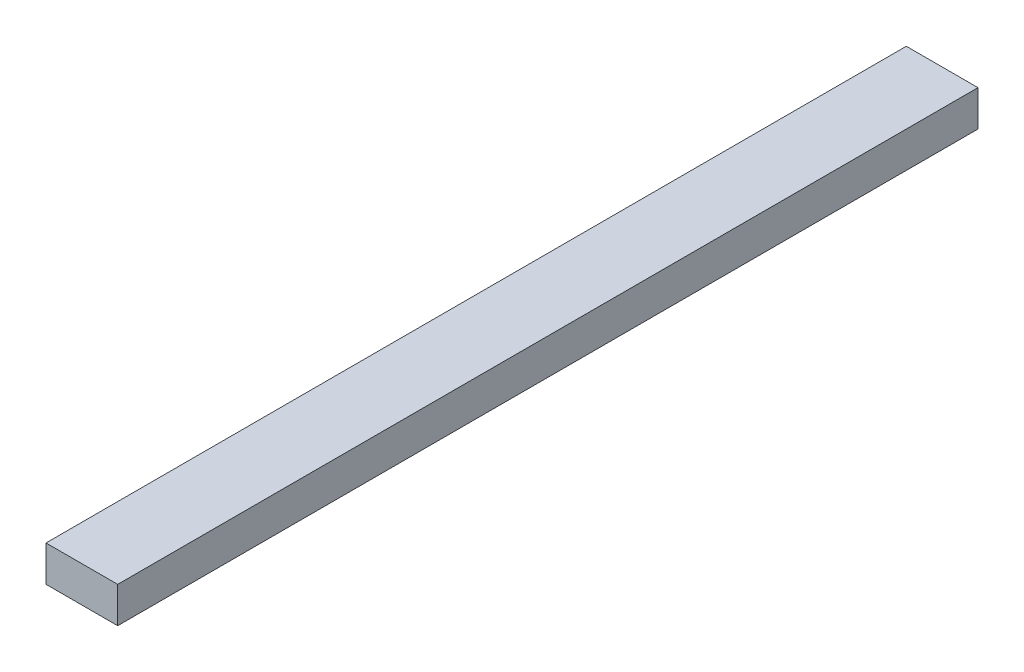
SolidWorks part; units mm, degrees
ref_plane "Front Plane" through (0, 0, 0) normal (0, 0, 1) x (1, 0, 0)
ref_plane "Top Plane" through (0, 0, 0) normal (0, 1, 0) x (1, 0, 0)
ref_plane "Right Plane" through (0, 0, 0) normal (1, 0, 0) x (0, 0, -1)
sketch "Sketch1" plane through (0, 0, 0) normal (0, 0, 1) x (1, 0, 0)
  line L1 (0, 0) -> (101.6, 0)
  line L2 (0, 0) -> (0, 50.8)
  line L3 (0, 50.8) -> (101.6, 50.8)
  line L4 (101.6, 0) -> (101.6, 50.8)
  dimension "D1" = 50.8
  dimension "D2" = 101.6
extrude "Boss-Extrude1" add sketch "Sketch1" along normal blind 1219.2 contours L2 L3 L4 L1
